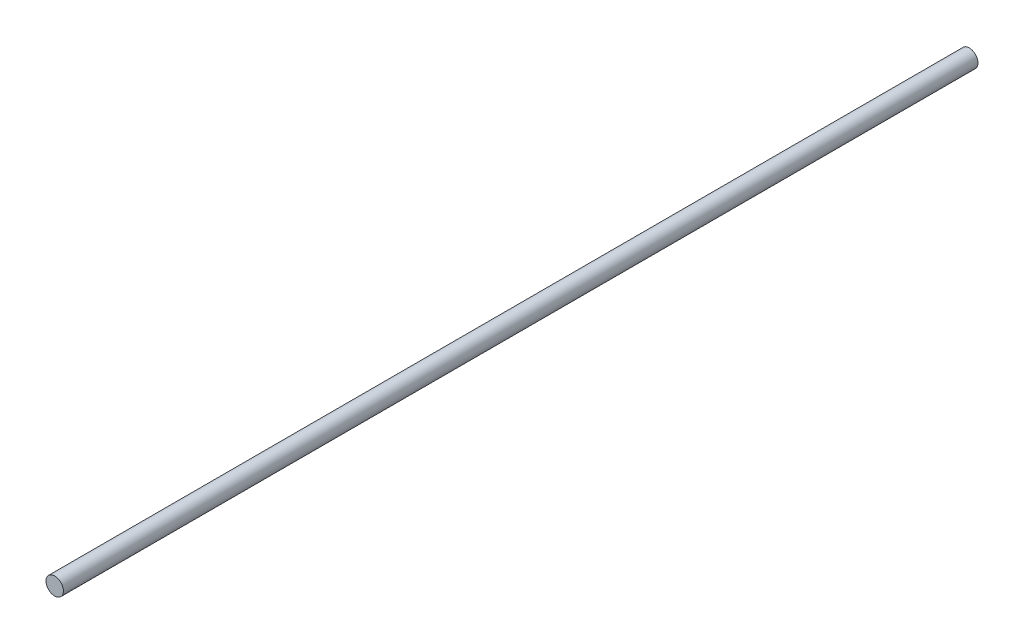
SolidWorks part; units mm, degrees
ref_plane "前视基准面" through (0, 0, 0) normal (0, 0, 1) x (1, 0, 0)
ref_plane "上视基准面" through (0, 0, 0) normal (0, 1, 0) x (1, 0, 0)
ref_plane "右视基准面" through (0, 0, 0) normal (1, 0, 0) x (0, 0, -1)
sketch "草图1" plane through (0, 0, 0) normal (0, 0, 1) x (1, 0, 0)
  circle A0 centre (0, 0) radius 2
  dimension "D1" = 4
extrude "凸台-拉伸1" add sketch "草图1" along normal blind 210
